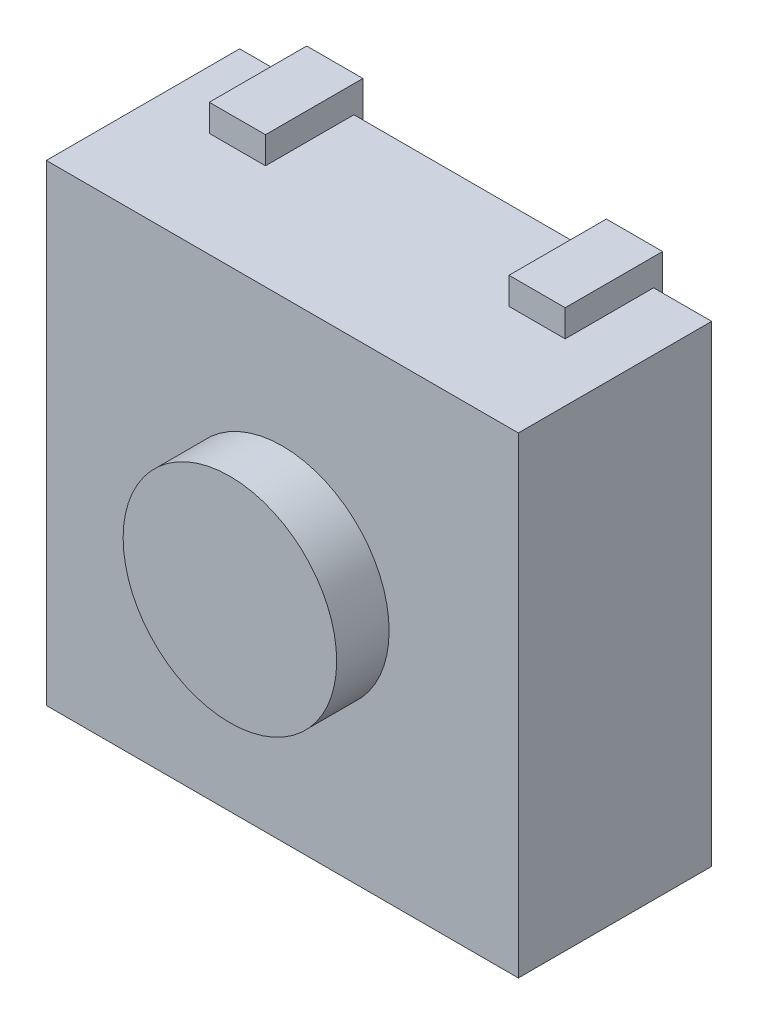
SolidWorks part; units mm, degrees
ref_plane "Ebene vorne" through (0, 0, 0) normal (0, 0, 1) x (1, 0, 0)
ref_plane "Ebene oben" through (0, 0, 0) normal (0, 1, 0) x (1, 0, 0)
ref_plane "Ebene rechts" through (0, 0, 0) normal (1, 0, 0) x (0, 0, -1)
sketch "Skizze1" plane through (0, 0, 0) normal (0, 0, 1) x (1, 0, 0)
  line L1 (-3.15, -3.15) -> (3.15, -3.15)
  line L2 (-3.15, -3.15) -> (-3.15, 3.15)
  line L3 (-3.15, 3.15) -> (3.15, 3.15)
  line L4 (3.15, -3.15) -> (3.15, 3.15)
  line L5 (-3.15, -3.15) -> (3.15, 3.15) construction
  line L6 (-3.15, 3.15) -> (3.15, -3.15) construction
  point P0 (0, 0)
  dimension "D1" = 6.3
extrude "Aufsatz-Linear austragen1" add sketch "Skizze1" along normal blind 2.7
sketch "Skizze2" plane through (0, 0, 0) normal (0, 0, 1) x (1, 0, 0)
  circle A0 centre (0, 0) radius 1.425
  dimension "D1" = 2.85
extrude "Aufsatz-Linear austragen2" add sketch "Skizze2" along normal blind 3.4
other "Fläche verschieben1" face at (0, 0, 0) parameters "D1"=0.12
sketch "Skizze3" plane through (0, 0, 0) normal (0, 0, 1) x (1, 0, 0)
  line L3 (-2.375, 3.51) -> (-1.625, 3.51)
  line L7 (0, 5.6347) -> (0, -5.5317) construction
  line L8 (-5.506, 0) -> (4.5283, 0) construction
  line L9 (-2.375, 3.51) -> (-2.375, 1.9)
  line L10 (-2.375, 1.9) -> (-1.625, 1.9)
  line L11 (-1.625, 1.9) -> (-1.625, 3.51)
  dimension "D1" = 0.75
  dimension "D2" = 2.375
  dimension "D4" = 1.9
  dimension "D5" = 3.51
extrude "Aufsatz-Linear austragen3" add sketch "Skizze3" along normal blind 1.3
mirror "Spiegeln1" about plane through (0, 0, 0) normal (0, 1, 0) of "Aufsatz-Linear austragen3" second plane through (0, 0, 0) second plane normal (1, 0, 0)
